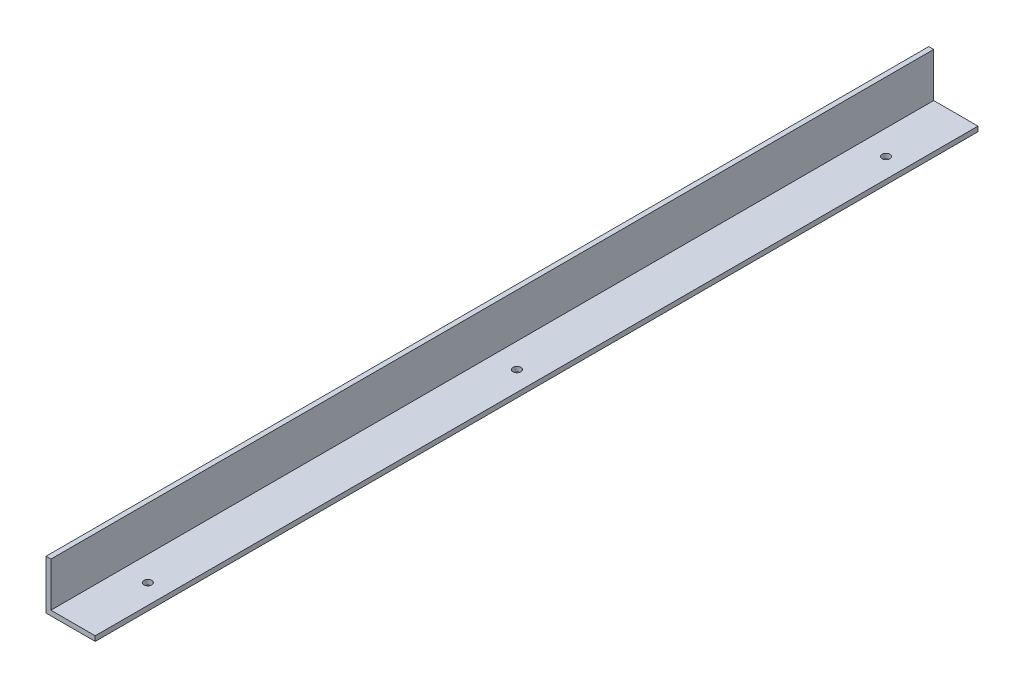
SolidWorks part; units mm, degrees
material "ASTM A36 Steel"
ref_plane "Front Plane" through (0, 0, 0) normal (0, 0, 1) x (1, 0, 0)
ref_plane "Top Plane" through (0, 0, 0) normal (0, 1, 0) x (1, 0, 0)
ref_plane "Right Plane" through (0, 0, 0) normal (1, 0, 0) x (0, 0, -1)
sketch "Sketch1" plane through (0, 0, 0) normal (0, 0, 1) x (1, 0, 0)
  line L0 (-18.9248, 31.4697) -> (-18.9248, -13.5303)
  line L1 (-18.9248, -13.5303) -> (26.0752, -13.5303)
  line L2 (26.0752, -13.5303) -> (26.0752, -18.5303)
  line L3 (26.0752, -18.5303) -> (-23.9248, -18.5303)
  line L4 (-23.9248, -18.5303) -> (-23.9248, 31.4697)
  line L5 (-23.9248, 31.4697) -> (-18.9248, 31.4697)
  dimension "D1" = 50
  dimension "D2" = 50
  dimension "D3" = 5
  dimension "D4" = 5
extrude "Boss-Extrude1" add sketch "Sketch1" along normal mid plane 897
sketch "Sketch2" plane through (0, -18.5303, 0) normal (0, -1, 0) x (1, 0, 0)
  line L0 (-23.9248, 448.5) -> (26.0752, 448.5) construction
  line L1 (26.0752, 448.5) -> (26.0752, -448.5) construction
  circle A0 centre (6.0752, 375) radius 4
  dimension "D1" = 8
  dimension "D2" = 73.5
  dimension "D3" = 20
extrude "Cut-Extrude1" cut sketch "Sketch2" against normal blind 10
pattern_linear "LPattern1" count 3 spacing 375 along (0, 0, -1) of "Cut-Extrude1"
